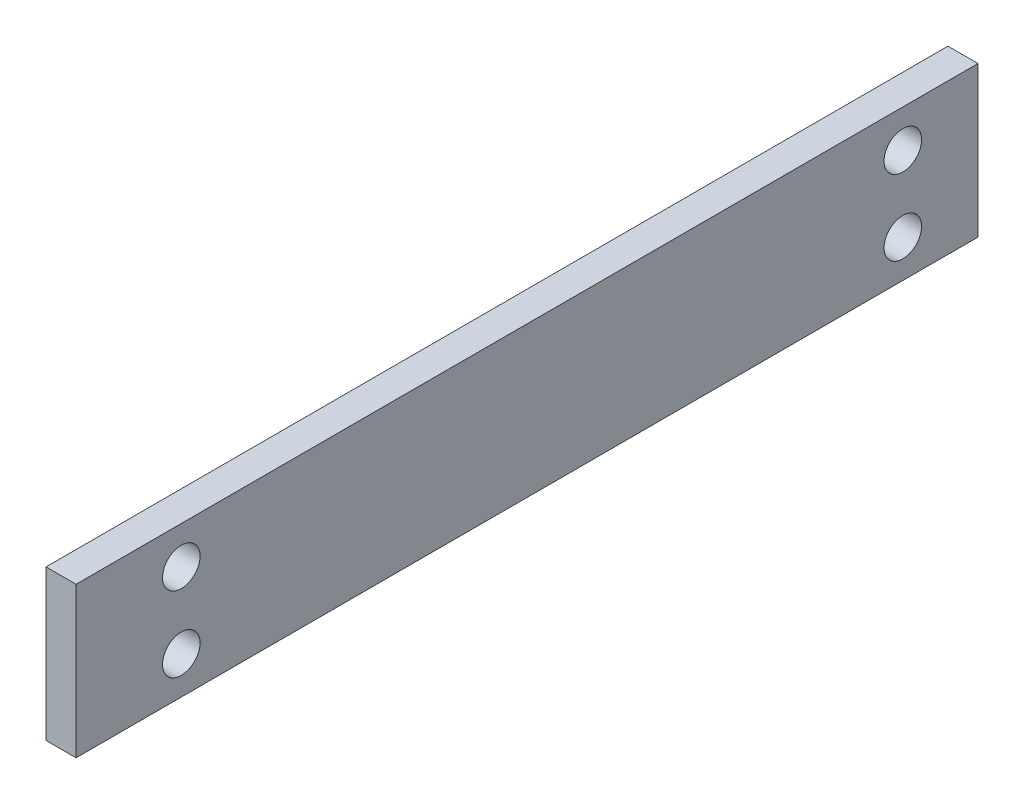
SolidWorks part; units mm, degrees
ref_plane "Спереди" through (0, 0, 0) normal (0, 0, 1) x (1, 0, 0)
ref_plane "Сверху" through (0, 0, 0) normal (0, 1, 0) x (1, 0, 0)
ref_plane "Справа" through (0, 0, 0) normal (1, 0, 0) x (0, 0, -1)
sketch "Эскиз1" plane through (0, 0, 0) normal (1, 0, 0) x (0, 0, -1)
  line L0 (110, 20) -> (110, 0) construction
  line L1 (0, 0) -> (120, 0)
  line L2 (0, 0) -> (0, 20)
  line L3 (0, 20) -> (120, 20)
  line L4 (120, 0) -> (120, 20)
  line L5 (26, 20) -> (26, 0) construction
  line L6 (14, 20) -> (14, 0) construction
  circle A0 centre (110, 15) radius 2.5
  circle A1 centre (110, 5) radius 2.5
  circle A2 centre (14, 15) radius 2.5
  circle A3 centre (14, 5) radius 2.5
  dimension "D4" = 5
  dimension "D5" = 12
  dimension "D1" = 20
  dimension "D2" = 120
  dimension "D3" = 10
  dimension "D6" = 5
  dimension "D7" = 5
  dimension "D8" = 94
extrude "Бобышка-Вытянуть1" add sketch "Эскиз1" along normal blind 4
